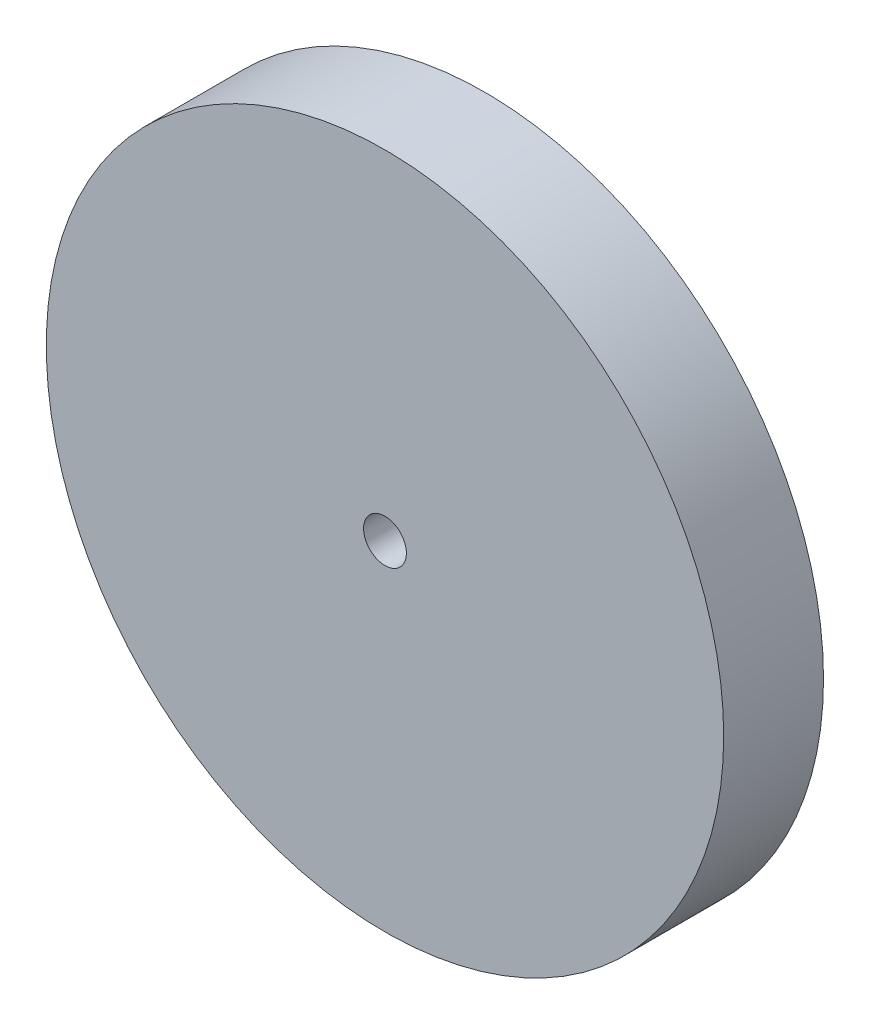
SolidWorks part; units mm, degrees
ref_plane "前视基准面" through (0, 0, 0) normal (0, 0, 1) x (1, 0, 0)
ref_plane "上视基准面" through (0, 0, 0) normal (0, 1, 0) x (1, 0, 0)
ref_plane "右视基准面" through (0, 0, 0) normal (1, 0, 0) x (0, 0, -1)
sketch "草图1" plane through (0, 0, 0) normal (0, 0, 1) x (1, 0, 0)
  circle A0 centre (0, 0) radius 47.5
  circle A1 centre (0, 0) radius 3
  dimension "D1" = 95
  dimension "D2" = 6
extrude "凸台-拉伸1" add sketch "草图1" along normal blind 14
sketch "草图2" plane through (0, 0, 0) normal (0, 0, -1) x (-1, 0, 0)
  circle A0 centre (0, 0) radius 9
  circle A1 centre (0, 0) radius 3 construction
  circle A2 centre (0, 0) radius 3
  dimension "D1" = 18
extrude "凸台-拉伸2" add sketch "草图2" along normal blind 6
